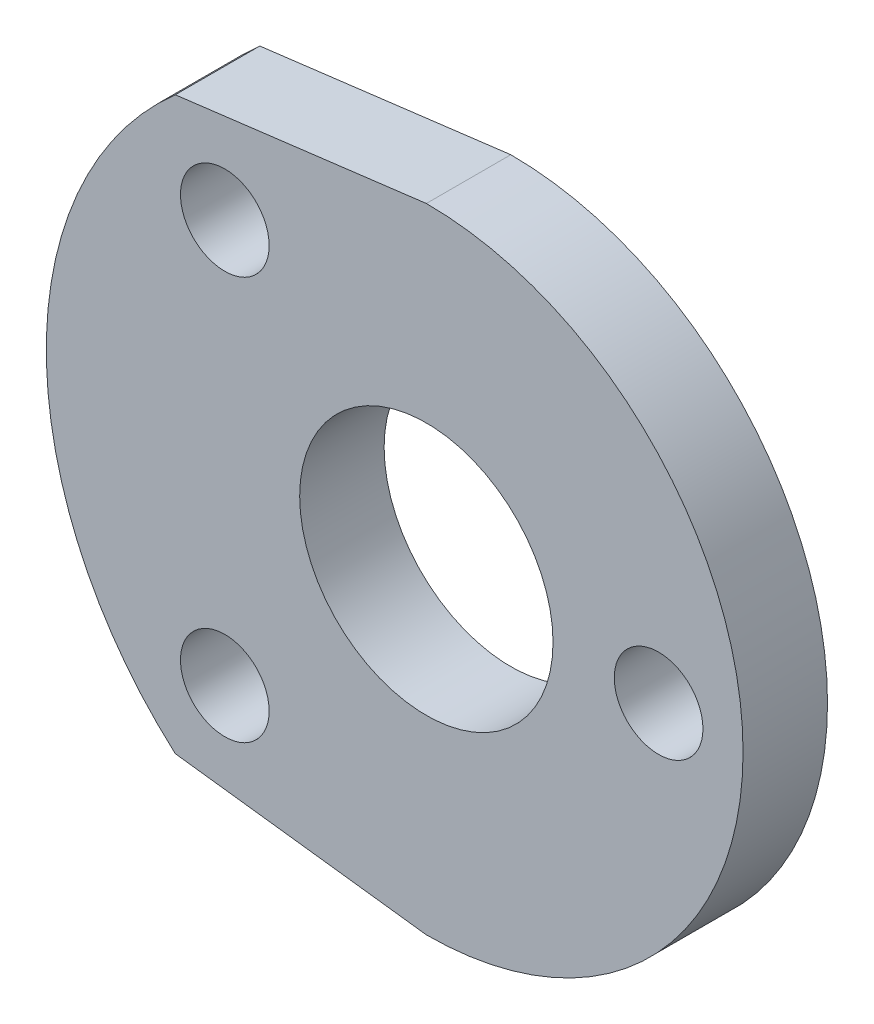
SolidWorks part; units mm, degrees
ref_plane "Plan de face" through (0, 0, 0) normal (0, 0, 1) x (1, 0, 0)
ref_plane "Plan de dessus" through (0, 0, 0) normal (0, 1, 0) x (1, 0, 0)
ref_plane "Plan de droite" through (0, 0, 0) normal (1, 0, 0) x (0, 0, -1)
sketch "Esquisse1" plane through (0, 0, 0) normal (0, 0, 1) x (1, 0, 0)
  line L0 (-96.8355, 0) -> (73.9282, 0) construction
  line L1 (0, 0) -> (-63.7892, 63.7892) construction
  line L2 (-10.8118, 5.615) -> (-10.8118, -6.75) construction
  line L3 (-20, -5) -> (-20, 5)
  line L4 (-20, 5) -> (0, 7.5)
  line L5 (0, -7.5) -> (-20, -5)
  circle A0 centre (0, 0) radius 7.5
  circle A1 centre (0, 0) radius 6.75 construction
  circle A2 centre (5.5, 0) radius 1.05
  circle A3 centre (-4.773, 4.773) radius 1.05
  circle A4 centre (-4.773, -4.773) radius 1.05
  arc A5 (-5.9452, 6.7569) -> (-5.9452, -6.7569) centre (0, 0) ccw
  circle A6 centre (0, 0) radius 3
  point P18 (-20, 0)
  dimension "D1" = 45
  dimension "D2" = 2.1
  dimension "D3" = 15
  dimension "D4" = 13.5
  dimension "D8" = 9
  dimension "D9" = 6
  dimension "D5" = 5.5
  dimension "D6" = 10
  dimension "D7" = 20
extrude "Boss.-Extru.1" add sketch "Esquisse1" along normal blind 2 contours A0 A4 L5 L4 A3 A2 | L4 A5 L5 A0 A4 A3
